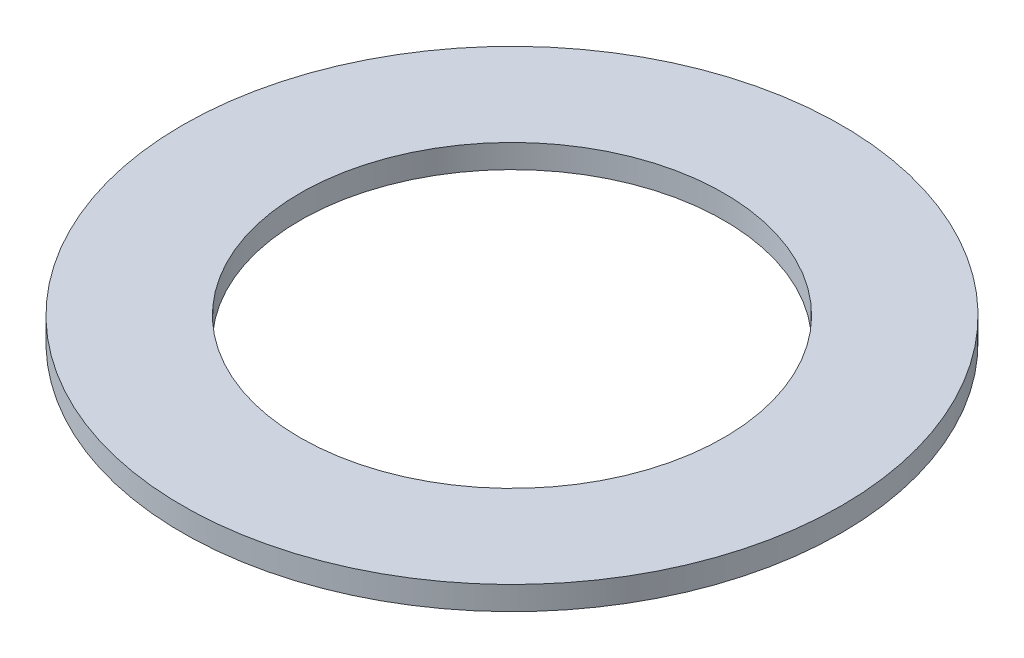
SolidWorks part; units mm, degrees
material "Plain Carbon Steel"
ref_plane "Front Plane" through (0, 0, 0) normal (0, 0, 1) x (1, 0, 0)
ref_plane "Top Plane" through (0, 0, 0) normal (0, 1, 0) x (1, 0, 0)
ref_plane "Right Plane" through (0, 0, 0) normal (1, 0, 0) x (0, 0, -1)
sketch "Sketch1" plane through (0, 0, 0) normal (0, 1, 0) x (1, 0, 0)
  circle A0 centre (0, 0) radius 9
  dimension "D1" = 18
extrude "Extrude-Thin1" add sketch "Sketch1" along normal blind 1 thin
